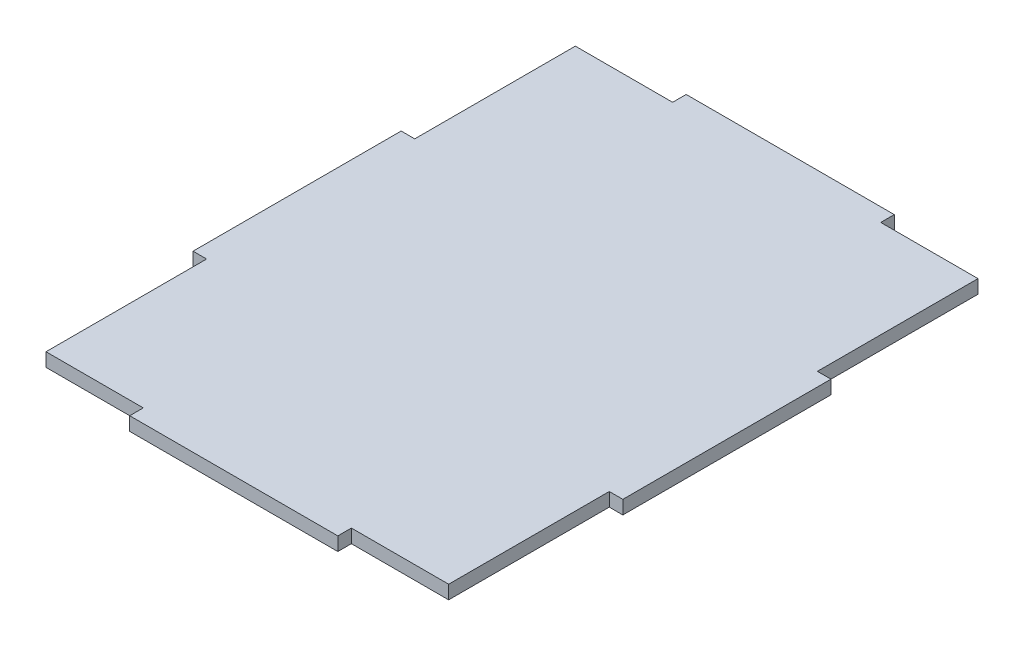
SolidWorks part; units mm, degrees
ref_plane "Alzado" through (0, 0, 0) normal (0, 0, 1) x (1, 0, 0)
ref_plane "Planta" through (0, 0, 0) normal (0, 1, 0) x (1, 0, 0)
ref_plane "Vista lateral" through (0, 0, 0) normal (1, 0, 0) x (0, 0, -1)
sketch "Croquis1" plane through (0, 0, 0) normal (0, 1, 0) x (1, 0, 0)
  line L0 (3, 38.5) -> (3, 3)
  line L1 (3, 3) -> (24.5, 3)
  line L2 (24.5, 3) -> (24.5, 0)
  line L3 (24.5, 0) -> (70.5, 0)
  line L4 (70.5, 0) -> (70.5, 3)
  line L5 (70.5, 3) -> (92, 3)
  line L6 (92, 3) -> (92, 38.5)
  line L7 (92, 38.5) -> (95, 38.5)
  line L8 (95, 38.5) -> (95, 84.5)
  line L9 (95, 84.5) -> (92, 84.5)
  line L10 (92, 84.5) -> (92, 120)
  line L11 (92, 120) -> (70.5, 120)
  line L12 (70.5, 120) -> (70.5, 123)
  line L13 (70.5, 123) -> (24.5, 123)
  line L14 (24.5, 123) -> (24.5, 120)
  line L15 (24.5, 120) -> (3, 120)
  line L16 (3, 120) -> (3, 84.5)
  line L17 (3, 84.5) -> (0, 84.5)
  line L18 (0, 84.5) -> (0, 38.5)
  line L19 (0, 38.5) -> (3, 38.5)
  line L20 (47.5, 123) -> (47.5, 0) construction
  line L21 (0, 61.5) -> (95, 61.5) construction
  line L22 (24.5, 0) -> (0, 0) construction
  line L23 (0, 0) -> (0, 38.5) construction
  point P23 (0, 61.5)
  point P24 (47.5, 61.5)
  point P25 (95, 61.5)
  point P29 (47.5, 61.5)
  dimension "D1" = 3
  dimension "D2" = 3
  dimension "D3" = 3
  dimension "D4" = 3
  dimension "D5" = 46
  dimension "D6" = 123
  dimension "D7" = 46
  dimension "D8" = 95
extrude "Saliente-Extruir1" add sketch "Croquis1" along normal blind 3
